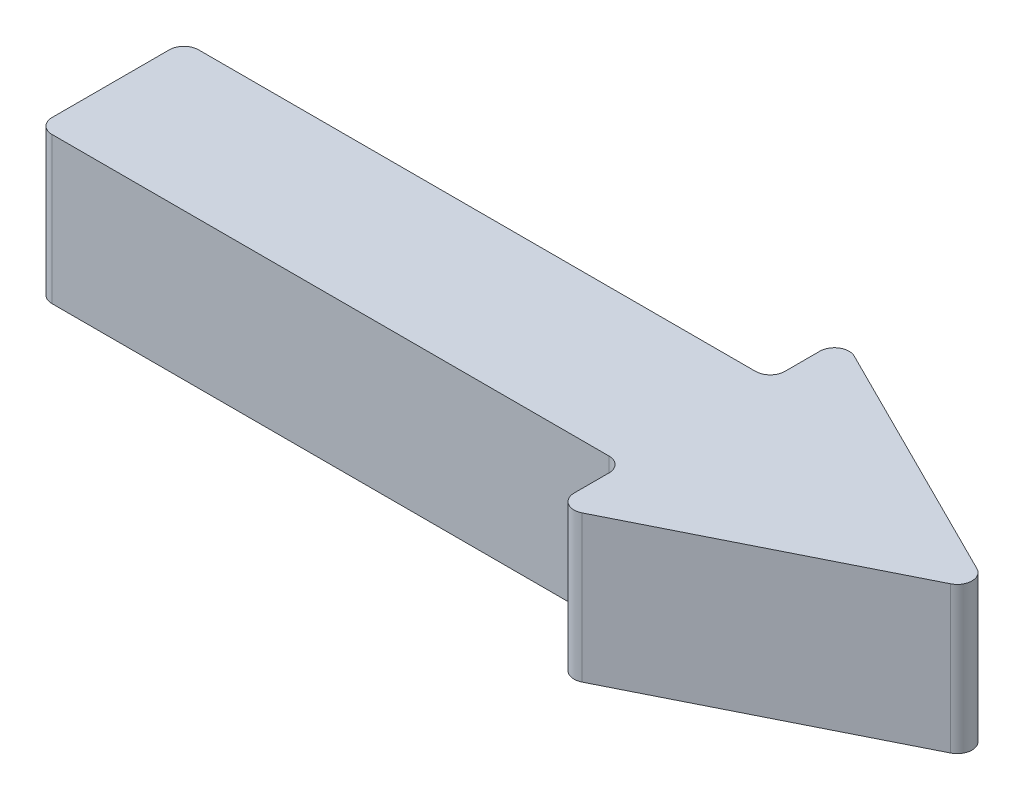
SolidWorks part; units mm, degrees
material "Acrylic (Medium-high impact)"
ref_plane "Front Plane" through (0, 0, 0) normal (0, 0, 1) x (1, 0, 0)
ref_plane "Top Plane" through (0, 0, 0) normal (0, 1, 0) x (1, 0, 0)
ref_plane "Right Plane" through (0, 0, 0) normal (1, 0, 0) x (0, 0, -1)
sketch "Sketch1" plane through (0, 0, 0) normal (0, 1, 0) x (1, 0, 0)
  line L0 (0, 3.175) -> (38.1, 3.175) construction
  line L1 (0, 0) -> (25.4, 0)
  line L2 (0, 0) -> (0, 6.35)
  line L3 (0, 6.35) -> (25.4, 6.35)
  line L4 (25.4, 0) -> (25.4, 6.35)
  line L5 (25.4, -3.175) -> (25.4, 9.525)
  line L6 (25.4, 9.525) -> (38.1, 3.175)
  line L7 (38.1, 3.175) -> (25.4, -3.175)
  point P10 (25.4, 3.175)
  dimension "D1" = 6.35
  dimension "D2" = 25.4
  dimension "D3" = 38.1
  dimension "D4" = 12.7
extrude "Boss-Extrude1" add sketch "Sketch1" along normal blind 6.35 contours L2 L0 L5 L3 | L0 L2 L1 L4 | L5 L0 L6 | L0 L4 L5 L7
sketch "Sketch2" plane through (0, 0, 0) normal (-1, 0, 0) x (0, 0, 1)
  line L0 (-3.175, 0) -> (-3.175, 6.35) construction
  line L1 (0, 6.35) -> (-6.35, 6.35) construction
  line L2 (-6.35, 3.175) -> (0, 3.175) construction
  line L3 (-6.35, 6.35) -> (-6.35, 0) construction
  line L4 (0, 6.35) -> (0, 0) construction
  circle A0 centre (-3.175, 3.175) radius 2.4003
  dimension "D1" = 4.8006
extrude "Cut-Extrude1" cut sketch "Sketch2" against normal blind 8.89
fillet "Fillet1" radius 0.635 7 edges at (25.4, 3.175, -6.35) (25.4, 3.175, 0) (25.4, 3.175, 3.175) (25.4, 3.175, -9.525) (38.1, 3.175, -3.175) (0, 3.175, 0) (0, 3.175, -6.35)
sketch "Sketch3" plane through (0, 0, 0) normal (0, -1, 0) x (1, 0, 0)
  line L0 (0, -3.175) -> (37.3151, -3.175) construction
  line L1 (0, -0.635) -> (0, -5.715) construction
  line L2 (18.6575, -6.35) -> (18.6575, 0)
  line L3 (0.635, 0) -> (24.765, 0) construction
  arc A0 (36.9641, -3.743) -> (36.9641, -2.607) centre (36.6801, -3.175) ccw construction
  circle A1 centre (11.0375, -3.175) radius 0.889
  circle A2 centre (26.2775, -3.175) radius 0.889
  point P12 (18.6575, -3.175)
  dimension "D1" = 1.778
  dimension "D2" = 7.62
extrude "Cut-Extrude2" cut sketch "Sketch3" against normal blind 3.81 contours A1 L0 | L0 A1 | L0 A2 | A2 L0
